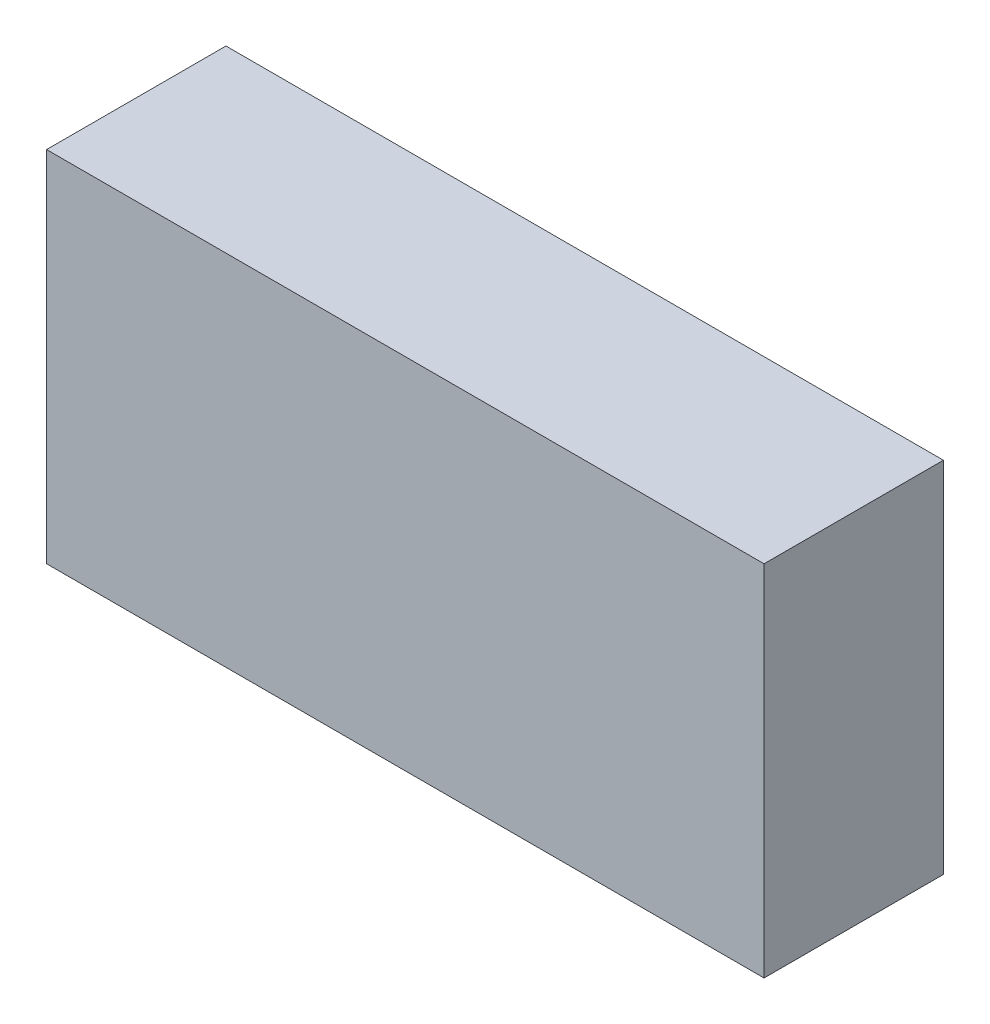
SolidWorks part; units mm, degrees
ref_plane "前视基准面" through (0, 0, 0) normal (0, 0, 1) x (1, 0, 0)
ref_plane "上视基准面" through (0, 0, 0) normal (0, 1, 0) x (1, 0, 0)
ref_plane "右视基准面" through (0, 0, 0) normal (1, 0, 0) x (0, 0, -1)
other "Configuration Table"
sketch "草图1" plane through (0, 0, 0) normal (0, 0, 1) x (1, 0, 0)
  line L1 (-20000, -10000) -> (20000, -10000)
  line L2 (-20000, -10000) -> (-20000, 10000)
  line L3 (-20000, 10000) -> (20000, 10000)
  line L4 (20000, -10000) -> (20000, 10000)
extrude "凸台-拉伸1" add sketch "草图1" against normal blind 10000
